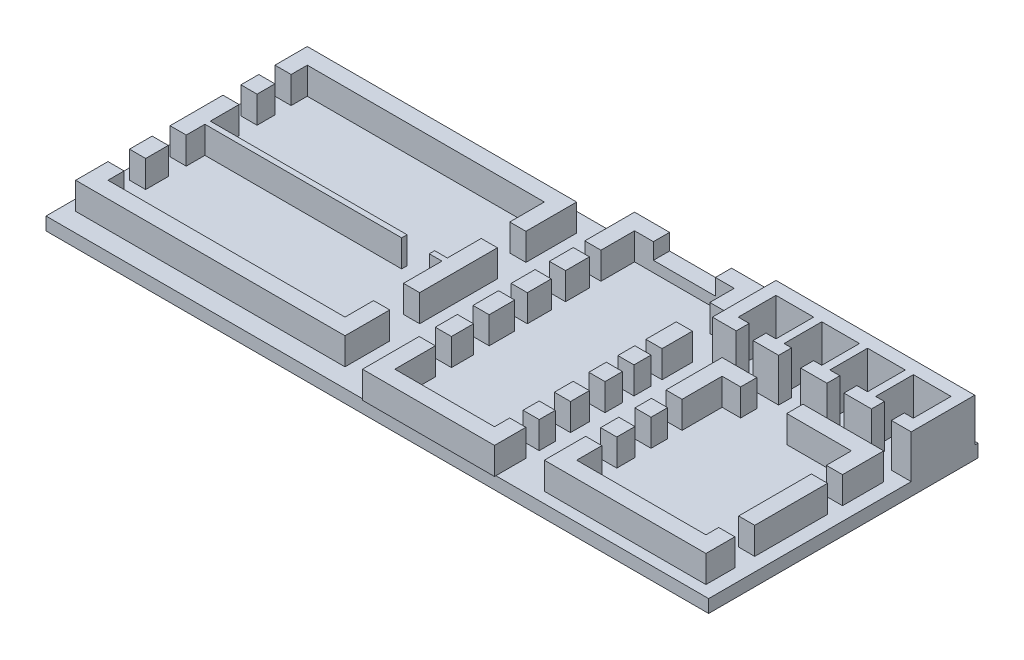
SolidWorks part; units mm, degrees
ref_plane "Front Plane" through (0, 0, 0) normal (0, 0, 1) x (1, 0, 0)
ref_plane "Top Plane" through (0, 0, 0) normal (0, 1, 0) x (1, 0, 0)
ref_plane "Right Plane" through (0, 0, 0) normal (1, 0, 0) x (0, 0, -1)
sketch "Sketch1" plane through (0, 0, 0) normal (0, 1, 0) x (1, 0, 0)
  line L1 (0, 0) -> (123, 0)
  line L2 (0, 0) -> (0, -50)
  line L3 (0, -50) -> (123, -50)
  line L4 (123, 0) -> (123, -50)
  dimension "D1" = 123
  dimension "D2" = 50
extrude "Boss-Extrude1" add sketch "Sketch1" along normal blind 2.4
sketch "Sketch2" plane through (0, 2.4, 0) normal (0, 1, 0) x (1, 0, 0)
  line L0 (0, -50) -> (123, -50) construction
  line L1 (5, -6.5) -> (49, -6.5)
  line L2 (5, -6.5) -> (5, -24.5)
  line L3 (5, -43.5) -> (49, -43.5)
  line L4 (49, -6.5) -> (49, -24.5)
  line L5 (0, 0) -> (0, -50) construction
  line L6 (5, -24.5) -> (49, -24.5)
  line L7 (5, -25.5) -> (49, -25.5)
  line L8 (2, -3.5) -> (52, -3.5)
  line L9 (52, -3.5) -> (52, -46.5)
  line L10 (2, -46.5) -> (52, -46.5)
  line L11 (2, -3.5) -> (2, -46.5)
  line L12 (49, -25.5) -> (49, -43.5)
  line L13 (5, -25.5) -> (5, -43.5)
  line L14 (49, -6.5) -> (49, -43.5) construction
  line L16 (5, -6.5) -> (5, -43.5) construction
  dimension "D1" = 37
  dimension "D2" = 6.5
  dimension "D3" = 5
  dimension "D4" = 18
  dimension "D5" = 18
  dimension "D7" = 44
  dimension "D6" = 3
extrude "Boss-Extrude2" add sketch "Sketch2" along normal blind 5
sketch "Sketch3" plane through (0, 2.4, 0) normal (0, 1, 0) x (1, 0, 0)
  line L0 (123, 0) -> (0, 0) construction
  line L1 (62, -2.75) -> (80.5, -2.75)
  line L2 (62, -2.75) -> (62, -47.25)
  line L3 (62, -47.25) -> (80.5, -47.25)
  line L4 (80.5, -2.75) -> (80.5, -47.25)
  line L5 (52, -46.5) -> (52, -3.5) construction
  line L6 (59, 0.25) -> (83.5, 0.25)
  line L7 (83.5, 0.25) -> (83.5, -50.25)
  line L8 (59, -50.25) -> (83.5, -50.25)
  line L9 (59, 0.25) -> (59, -50.25)
  dimension "D1" = 44.5
  dimension "D2" = 18.5
  dimension "D3" = 2.75
  dimension "D4" = 10
  dimension "D5" = 3
extrude "Boss-Extrude3" add sketch "Sketch3" along normal blind 5
sketch "Sketch4" plane through (0, 7.4, 0) normal (0, 1, 0) x (1, 0, 0)
  line L0 (83.5, 0.25) -> (59, 0.25) construction
  line L1 (65.5, 0.25) -> (77, 0.25)
  line L2 (65.5, 0.25) -> (65.5, -2.75)
  line L3 (65.5, -2.75) -> (77, -2.75)
  line L4 (77, 0.25) -> (77, -2.75)
  line L5 (80.5, -2.75) -> (62, -2.75) construction
  line L6 (62, -2.75) -> (62, -47.25) construction
  line L7 (80.5, -47.25) -> (80.5, -2.75) construction
  dimension "D1" = 3.5
  dimension "D2" = 3.5
extrude "Cut-Extrude2" cut sketch "Sketch4" against normal blind 3
sketch "Sketch5" plane through (0, 2.4, 0) normal (0, 1, 0) x (1, 0, 0)
  line L0 (0, -50) -> (59, -50) construction
  line L1 (93.5, -18) -> (117.5, -18)
  line L2 (93.5, -18) -> (93.5, -45)
  line L3 (93.5, -45) -> (117.5, -45)
  line L4 (117.5, -18) -> (117.5, -45)
  line L5 (83.5, -50) -> (83.5, 0) construction
  line L6 (90.5, -15) -> (120.5, -15)
  line L7 (120.5, -15) -> (120.5, -48)
  line L8 (90.5, -48) -> (120.5, -48)
  line L9 (90.5, -15) -> (90.5, -48)
  dimension "D1" = 24
  dimension "D2" = 27
  dimension "D3" = 5
  dimension "D4" = 10
  dimension "D5" = 3
extrude "Boss-Extrude5" add sketch "Sketch5" along normal blind 5
sketch "Sketch6" plane through (0, 2.4, 0) normal (0, 1, 0) x (1, 0, 0)
  line L0 (83.5, -50.25) -> (83.5, 0.25) construction
  line L1 (88.5, -3) -> (95.5, -3)
  line L2 (88.5, -3) -> (88.5, -10)
  line L3 (88.5, -10) -> (95.5, -10)
  line L4 (95.5, -3) -> (95.5, -10)
  line L5 (123, 0) -> (83.5, 0) construction
  line L25 (95.5, -3) -> (95.5, -10)
  line L34 (97, -3) -> (104, -3)
  line L35 (104, -3) -> (104, -10)
  line L36 (97, -10) -> (104, -10)
  line L37 (97, -3) -> (97, -10)
  line L38 (105.5, -3) -> (112.5, -3)
  line L39 (112.5, -3) -> (112.5, -10)
  line L40 (105.5, -10) -> (112.5, -10)
  line L41 (105.5, -3) -> (105.5, -10)
  line L42 (114, -3) -> (121, -3)
  line L43 (121, -3) -> (121, -10)
  line L44 (114, -10) -> (121, -10)
  line L45 (114, -3) -> (114, -10)
  line L46 (123, -50) -> (123, 0) construction
  line L47 (123, -12.4) -> (86.1, -12.4)
  line L48 (123, -12.4) -> (123, -0.6)
  line L49 (123, -0.6) -> (86.1, -0.6)
  line L50 (86.1, -12.4) -> (86.1, -0.6)
  point P21 (98.5, 0)
  point P22 (98.5, -13)
  point P24 (95.5, 0)
  point P25 (108.5, 0)
  point P26 (108.5, -13)
  point P27 (95.5, -13)
  point P28 (105.5, 0)
  point P29 (118.5, 0)
  point P30 (118.5, -13)
  point P31 (105.5, -13)
  point P32 (115.5, 0)
  point P35 (115.5, -13)
  dimension "D1" = 7
  dimension "D2" = 7
  dimension "D3" = 5
  dimension "D4" = 3
  dimension "D6" = 2.4
  dimension "D7" = 2.4
  dimension "D8" = 2.4
  dimension "D5" = 4
extrude "Boss-Extrude6" add sketch "Sketch6" along normal blind 8
sketch "Sketch7" plane through (0, 7.4, 0) normal (0, 1, 0) x (1, 0, 0)
  line L0 (5, -24.5) -> (49, -24.5) construction
  line L1 (41.5178, -24.5) -> (46.6414, -24.5)
  line L2 (41.5178, -24.5) -> (41.5178, -25.5)
  line L3 (41.5178, -25.5) -> (46.6414, -25.5)
  line L4 (46.6414, -24.5) -> (46.6414, -25.5)
  line L5 (49, -25.5) -> (5, -25.5) construction
extrude "Cut-Extrude3" cut sketch "Sketch7" against normal blind 5
sketch "Sketch8" plane through (0, 7.4, 0) normal (0, 1, 0) x (1, 0, 0)
  line L0 (49, -24.5) -> (49, -6.5) construction
  line L1 (49, -12.9167) -> (52, -12.9167)
  line L2 (49, -12.9167) -> (49, -18.2112)
  line L3 (49, -18.2112) -> (52, -18.2112)
  line L4 (52, -12.9167) -> (52, -18.2112)
  line L5 (52, -46.5) -> (52, -3.5) construction
  line L6 (49, -43.5) -> (49, -25.5) construction
  line L7 (49, -32.6428) -> (52, -32.6428)
  line L8 (49, -32.6428) -> (49, -38.1934)
  line L9 (49, -38.1934) -> (52, -38.1934)
  line L10 (52, -32.6428) -> (52, -38.1934)
  line L11 (59, 0.25) -> (59, -50.25) construction
  line L12 (59, -8.9886) -> (62, -8.9886)
  line L13 (59, -8.9886) -> (59, -11.1235)
  line L14 (59, -11.1235) -> (62, -11.1235)
  line L15 (62, -8.9886) -> (62, -11.1235)
  line L16 (62, -2.75) -> (62, -47.25) construction
  line L17 (59, 0) -> (59, -50) construction
  line L18 (59, -15.564) -> (62, -15.564)
  line L19 (59, -15.564) -> (59, -18.2112)
  line L20 (59, -18.2112) -> (62, -18.2112)
  line L21 (62, -15.564) -> (62, -18.2112)
  line L22 (62, -2.75) -> (62, -47.25) construction
  line L23 (59, -22.6517) -> (62, -22.6517)
  line L24 (59, -22.6517) -> (59, -25)
  line L25 (59, -25) -> (62, -25)
  line L26 (62, -22.6517) -> (62, -25)
  line L27 (80.5, -47.25) -> (80.5, -2.75) construction
  line L28 (59, -29.7394) -> (62, -29.7394)
  line L29 (59, -29.7394) -> (59, -32.6428)
  line L30 (59, -32.6428) -> (62, -32.6428)
  line L31 (62, -29.7394) -> (62, -32.6428)
  line L32 (59, -36.7417) -> (62, -36.7417)
  line L33 (59, -36.7417) -> (59, -39.7305)
  line L34 (59, -39.7305) -> (62, -39.7305)
  line L35 (62, -36.7417) -> (62, -39.7305)
  line L36 (80.5, -7.2807) -> (83.5, -7.2807)
  line L37 (80.5, -7.2807) -> (80.5, -13.5145)
  line L38 (80.5, -13.5145) -> (83.5, -13.5145)
  line L39 (83.5, -7.2807) -> (83.5, -13.5145)
  line L40 (83.5, -50) -> (83.5, 0) construction
  line L41 (80.5, -47.25) -> (80.5, -2.75) construction
  line L42 (80.5, -19.1505) -> (83.5, -19.1505)
  line L43 (80.5, -19.1505) -> (80.5, -21.2)
  line L44 (80.5, -21.2) -> (83.5, -21.2)
  line L45 (83.5, -19.1505) -> (83.5, -21.2)
  line L46 (83.5, -50.25) -> (83.5, 0.25) construction
  line L47 (80.5, -24.3595) -> (83.5, -24.3595)
  line L48 (80.5, -24.3595) -> (80.5, -26.4944)
  line L49 (80.5, -26.4944) -> (83.5, -26.4944)
  line L50 (83.5, -24.3595) -> (83.5, -26.4944)
  line L51 (90.5, -15) -> (90.5, -48) construction
  line L52 (80.5, -29.7394) -> (83.5, -29.7394)
  line L53 (80.5, -29.7394) -> (80.5, -32.6428)
  line L54 (80.5, -32.6428) -> (83.5, -32.6428)
  line L55 (83.5, -29.7394) -> (83.5, -32.6428)
  line L56 (80.5, -36.1439) -> (83.5, -36.1439)
  line L57 (80.5, -36.1439) -> (80.5, -38.9619)
  line L58 (80.5, -38.9619) -> (83.5, -38.9619)
  line L59 (83.5, -36.1439) -> (83.5, -38.9619)
  line L60 (80.5, -41.9507) -> (83.5, -41.9507)
  line L61 (80.5, -41.9507) -> (80.5, -44.4271)
  line L62 (80.5, -44.4271) -> (83.5, -44.4271)
  line L63 (83.5, -41.9507) -> (83.5, -44.4271)
  line L64 (90.5, -25.427) -> (93.5, -25.427)
  line L65 (90.5, -25.427) -> (90.5, -28.1169)
  line L66 (90.5, -28.1169) -> (93.5, -28.1169)
  line L67 (93.5, -25.427) -> (93.5, -28.1169)
  line L68 (93.5, -18) -> (93.5, -45) construction
  line L69 (90.5, -15) -> (90.5, -48) construction
  line L70 (90.5, -31.1911) -> (93.5, -31.1911)
  line L71 (90.5, -31.1911) -> (90.5, -34.1799)
  line L72 (90.5, -34.1799) -> (93.5, -34.1799)
  line L73 (93.5, -31.1911) -> (93.5, -34.1799)
  line L74 (93.5, -18) -> (93.5, -45) construction
  line L75 (90.5, -37.5529) -> (93.5, -37.5529)
  line L76 (90.5, -37.5529) -> (90.5, -40.3282)
  line L77 (90.5, -40.3282) -> (93.5, -40.3282)
  line L78 (93.5, -37.5529) -> (93.5, -40.3282)
  line L79 (117.5, -45) -> (117.5, -18) construction
  line L80 (117.5, -38.9406) -> (120.5, -38.9406)
  line L81 (117.5, -38.9406) -> (117.5, -42.6339)
  line L82 (117.5, -42.6339) -> (120.5, -42.6339)
  line L83 (120.5, -38.9406) -> (120.5, -42.6339)
  line L84 (120.5, -48) -> (120.5, -15) construction
  line L85 (120.5, -48) -> (120.5, -15) construction
  line L86 (117.5, -22.6517) -> (120.5, -22.6517)
  line L87 (117.5, -22.6517) -> (117.5, -25.427)
  line L88 (117.5, -25.427) -> (120.5, -25.427)
  line L89 (120.5, -22.6517) -> (120.5, -25.427)
  line L90 (120.5, -15) -> (90.5, -15) construction
  line L91 (96.9385, -15) -> (105.5, -15)
  line L92 (96.9385, -15) -> (96.9385, -18)
  line L93 (96.9385, -18) -> (105.5, -18)
  line L94 (105.5, -15) -> (105.5, -18)
  line L95 (117.5, -18) -> (93.5, -18) construction
extrude "Cut-Extrude4" cut sketch "Sketch8" against normal blind 5
sketch "Sketch9" plane through (0, 10.4, 0) normal (0, 1, 0) x (1, 0, 0)
  line L22 (88.5, -10) -> (95.5, -10) construction
  line L23 (90.5244, -10) -> (93.6476, -10)
  line L24 (90.5244, -10) -> (90.5244, -12.4)
  line L25 (90.5244, -12.4) -> (93.6476, -12.4)
  line L26 (93.6476, -10) -> (93.6476, -12.4)
  line L27 (123, -12.4) -> (86.1, -12.4) construction
  line L28 (97, -10) -> (104, -10) construction
  line L29 (98.3931, -10) -> (102.4896, -10)
  line L30 (98.3931, -10) -> (98.3931, -12.4)
  line L31 (98.3931, -12.4) -> (102.4896, -12.4)
  line L32 (102.4896, -10) -> (102.4896, -12.4)
  line L33 (105.5, -10) -> (112.5, -10) construction
  line L34 (107.3569, -10) -> (110.5205, -10)
  line L35 (107.3569, -10) -> (107.3569, -12.4)
  line L36 (107.3569, -12.4) -> (110.5205, -12.4)
  line L37 (110.5205, -10) -> (110.5205, -12.4)
  line L38 (114, -10) -> (121, -10) construction
  line L39 (115.6311, -10) -> (119.3221, -10)
  line L40 (115.6311, -10) -> (115.6311, -12.4)
  line L41 (115.6311, -12.4) -> (119.3221, -12.4)
  line L42 (119.3221, -10) -> (119.3221, -12.4)
extrude "Cut-Extrude5" cut sketch "Sketch9" against normal blind 8
sketch "Sketch10" plane through (0, 7.4, 0) normal (0, 1, 0) x (1, 0, 0)
  line L0 (2, -3.5) -> (2, -46.5) construction
  line L1 (2, -9.5) -> (5, -9.5)
  line L2 (2, -9.5) -> (2, -12.5)
  line L3 (2, -12.5) -> (5, -12.5)
  line L4 (5, -9.5) -> (5, -12.5)
  line L5 (5, -6.5) -> (5, -24.5) construction
  line L6 (5, -25.5) -> (5, -43.5) construction
  line L7 (2, -15.8201) -> (5, -15.8201)
  line L8 (2, -15.8201) -> (2, -19.1505)
  line L9 (2, -19.1505) -> (5, -19.1505)
  line L10 (5, -15.8201) -> (5, -19.1505)
  line L11 (2, -28.9708) -> (5, -28.9708)
  line L12 (2, -28.9708) -> (2, -32.3012)
  line L13 (2, -32.3012) -> (5, -32.3012)
  line L14 (5, -28.9708) -> (5, -32.3012)
  line L15 (2, -3.5) -> (2, -46.5) construction
  line L16 (2, -36.5) -> (5, -36.5)
  line L17 (2, -36.5) -> (2, -40.5)
  line L18 (2, -40.5) -> (5, -40.5)
  line L19 (5, -36.5) -> (5, -40.5)
  line L20 (49, -6.5) -> (5, -6.5) construction
  line L21 (49, -6.5) -> (5, -6.5) construction
  line L22 (5, -43.5) -> (49, -43.5) construction
  point P28 (3.5, -40.5)
  dimension "D1" = 3
  dimension "D2" = 6
  dimension "D3" = 3
  dimension "D4" = 7
extrude "Cut-Extrude6" cut sketch "Sketch10" against normal blind 5
equation "\"D1@Sketch2\"=17*2+3"
equation "\"D2@Sketch2\"=\"D2@Sketch1\"/2-\"D1@Sketch2\"/2"
equation "\"D3@Sketch3\"=\"D2@Sketch1\"/2-\"D1@Sketch3\"/2"
